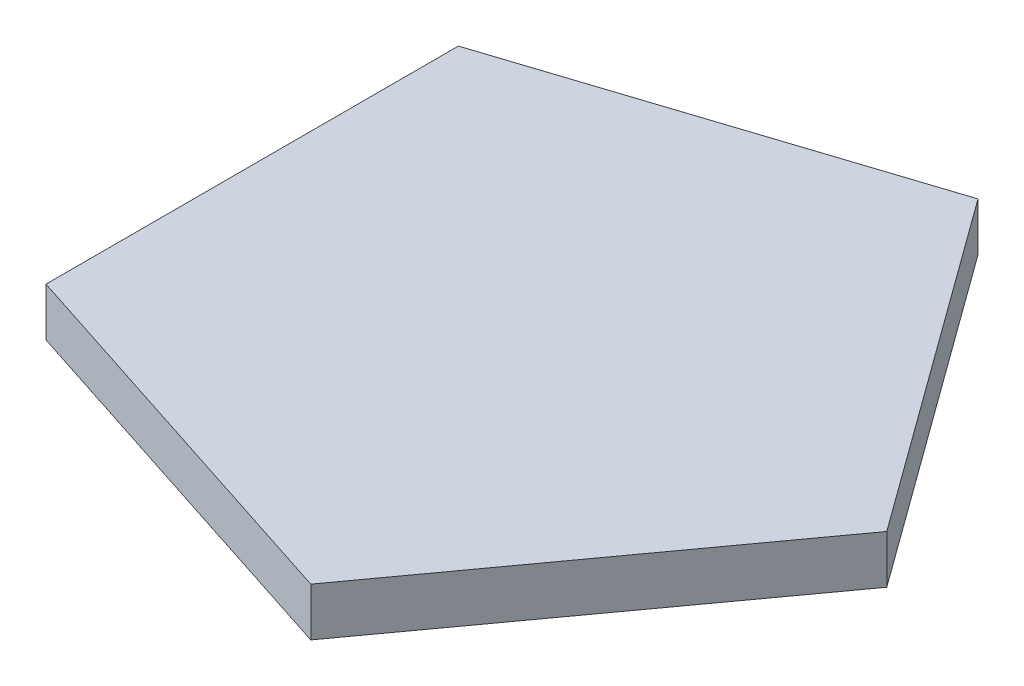
SolidWorks part; units mm, degrees
material "Pine"
ref_plane "Front Plane" through (0, 0, 0) normal (0, 0, 1) x (1, 0, 0)
ref_plane "Top Plane" through (0, 0, 0) normal (0, 1, 0) x (1, 0, 0)
ref_plane "Right Plane" through (0, 0, 0) normal (1, 0, 0) x (0, 0, -1)
sketch "Sketch1" plane through (0, 0, 0) normal (0, 1, 0) x (1, 0, 0)
  line L1 (54.4417, 0) -> (16.8234, 51.7771)
  line L2 (16.8234, 51.7771) -> (-44.0442, 32)
  line L3 (-44.0442, 32) -> (-44.0442, -32)
  line L4 (-44.0442, -32) -> (16.8234, -51.7771)
  line L5 (16.8234, -51.7771) -> (54.4417, 0)
  circle A0 centre (0, 0) radius 44.0442 construction
  dimension "D1" = 64
extrude "Boss-Extrude1" add sketch "Sketch1" along normal blind 7.5
